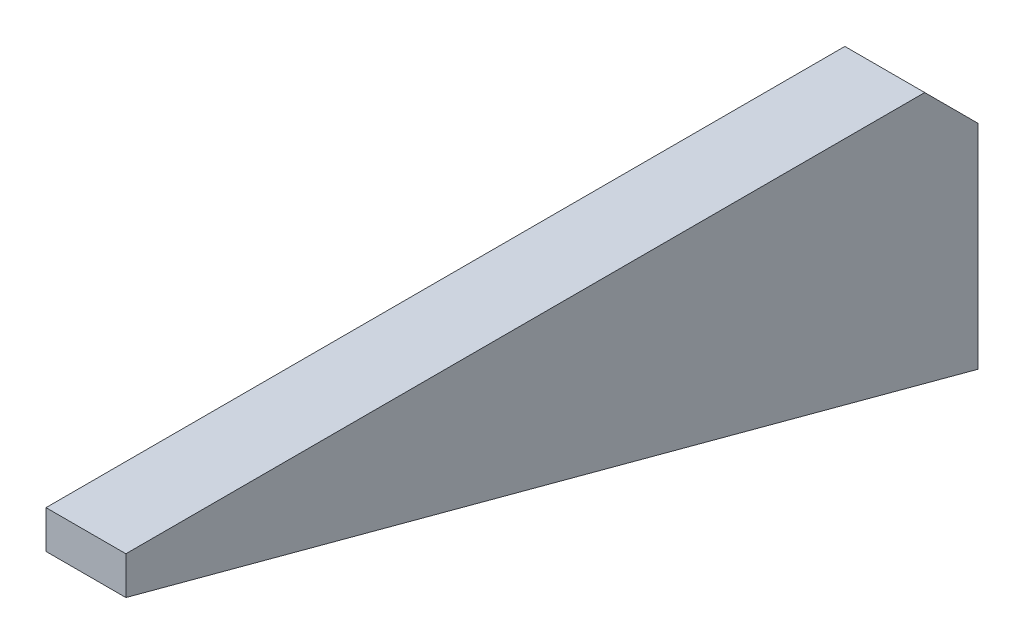
SolidWorks part; units mm, degrees
ref_plane "Front Plane" through (0, 0, 0) normal (1, 0, 0) x (0, 1, 0)
ref_plane "Top Plane" through (0, 0, 0) normal (0, 0, 1) x (0, 1, 0)
ref_plane "Right Plane" through (0, 0, 0) normal (0, 1, 0) x (-1, 0, 0)
sketch "Sketch2" plane through (0, 0, 0) normal (1, 0, 0) x (0, 1, 0)
  line L0 (-50, 0) -> (0, 0)
  line L1 (0, 0) -> (0, 160)
  line L2 (0, 160) -> (-7.1281, 160)
  line L3 (-7.1281, 160) -> (-50, 0)
  dimension "D1" = 50
  dimension "D2" = 160
  dimension "D3" = 75
extrude "Boss-Extrude1" add sketch "Sketch2" along normal mid plane 15
chamfer "Chamfer1" distance 10 angle 45 1 edges at (0, 0, 0)
